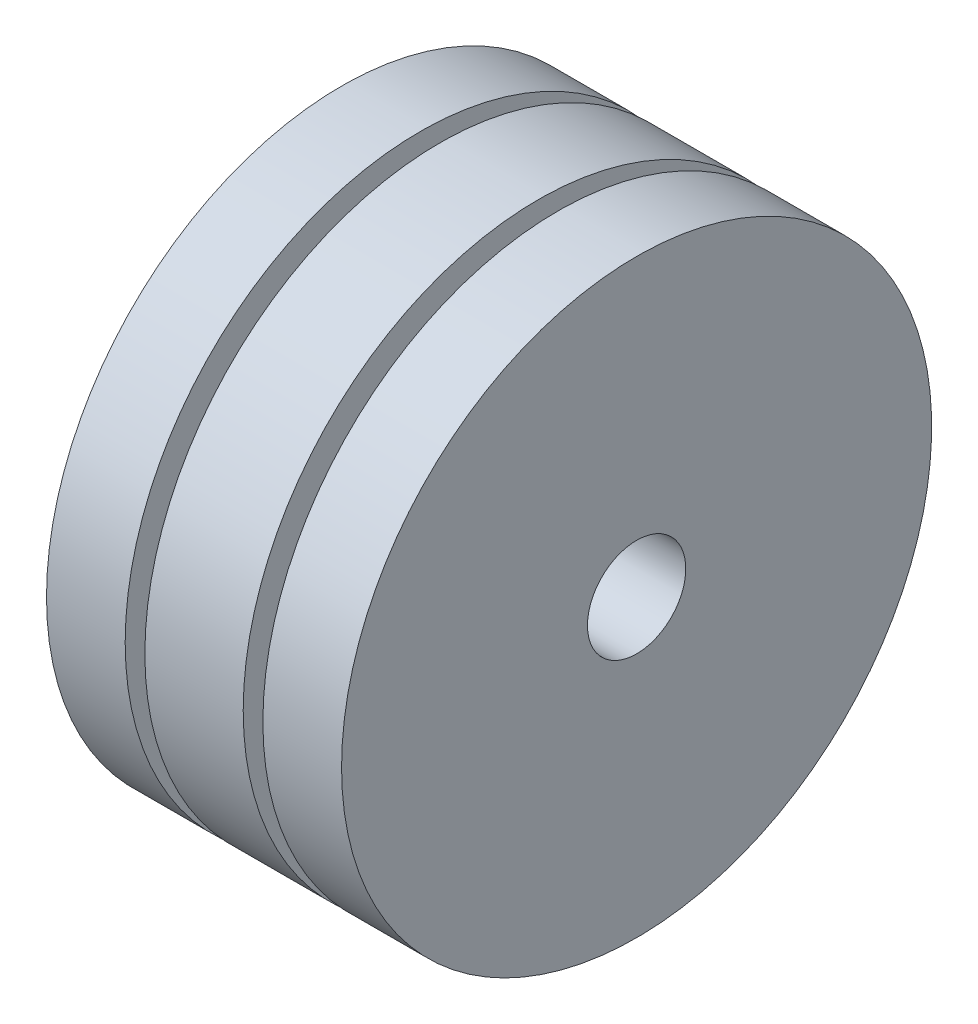
SolidWorks part; units mm, degrees
ref_plane "Front Plane" through (0, 0, 0) normal (0, 0, 1) x (1, 0, 0)
ref_plane "Top Plane" through (0, 0, 0) normal (0, 1, 0) x (1, 0, 0)
ref_plane "Right Plane" through (0, 0, 0) normal (1, 0, 0) x (0, 0, -1)
sketch "Sketch1" plane through (0, 0, 0) normal (0, 1, 0) x (1, 0, 0)
  line L0 (-5, -12.5) -> (5, -12.5)
  line L1 (-15, 12.5) -> (15, 12.5)
  line L2 (-15, 12.5) -> (-15, -12.5)
  line L3 (-15, -12.5) -> (-7, -12.5)
  line L4 (15, 12.5) -> (15, -12.5)
  line L5 (-15, 12.5) -> (15, -12.5) construction
  line L6 (-15, -12.5) -> (15, 12.5) construction
  line L8 (-7, -12.5) -> (-7, 7.5)
  line L9 (-7, 7.5) -> (-5, 7.5)
  line L10 (-5, -12.5) -> (-5, 7.5)
  line L12 (5, -12.5) -> (5, 7.5)
  line L13 (5, 7.5) -> (7, 7.5)
  line L14 (7, -12.5) -> (7, 7.5)
  line L15 (7, -12.5) -> (15, -12.5)
  line L16 (-32.4645, 17.5) -> (59.912, 17.5) construction
  point P0 (0, 0)
  dimension "D1" = 30
  dimension "D2" = 25
  dimension "D3" = 20
  dimension "D4" = 20
  dimension "D5" = 2
  dimension "D6" = 2
  dimension "D7" = 8
  dimension "D8" = 8
  dimension "D9" = 5
revolve "Revolve1" add sketch "Sketch1" angle 360 about L16
